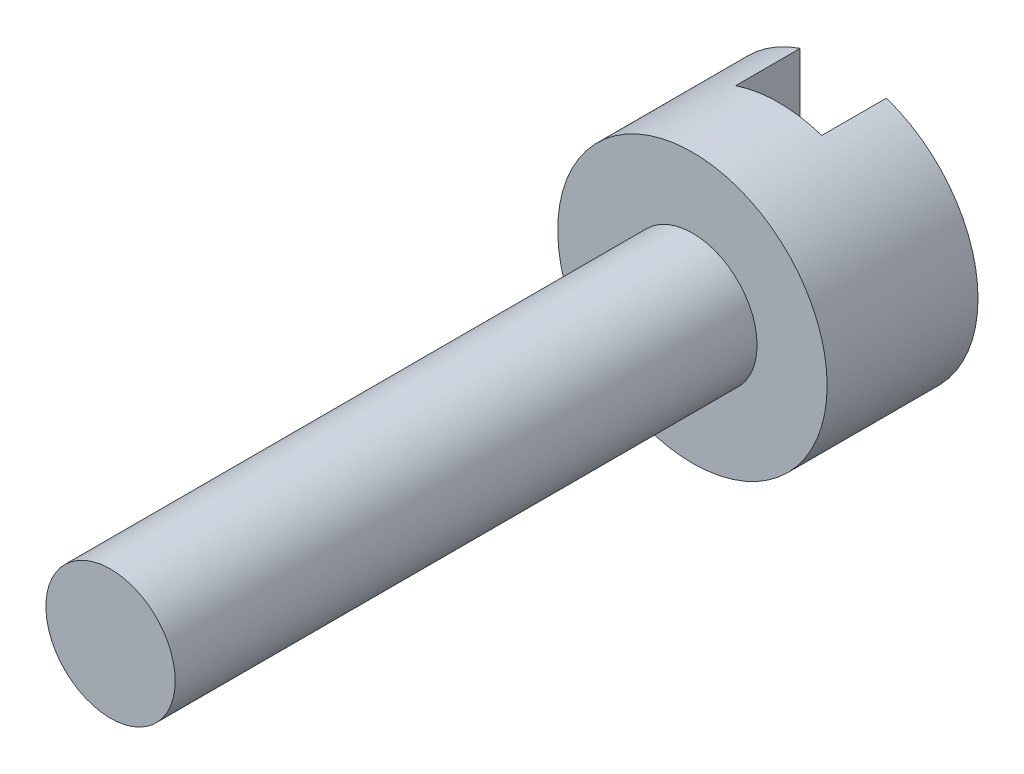
SolidWorks part; units mm, degrees
material "Plain Carbon Steel"
ref_plane "Front Plane" through (0, 0, 0) normal (0, 0, 1) x (1, 0, 0)
ref_plane "Top Plane" through (0, 0, 0) normal (0, 1, 0) x (1, 0, 0)
ref_plane "Right Plane" through (0, 0, 0) normal (1, 0, 0) x (0, 0, -1)
sketch "Sketch1" plane through (0, 0, 0) normal (0, 0, 1) x (1, 0, 0)
  circle A0 centre (0, 0) radius 0.625
  dimension "D1" = 1.25
extrude "Boss-Extrude1" add sketch "Sketch1" along normal blind 0.7
sketch "Sketch3" plane through (0, 0, 0.7) normal (0, 0, 1) x (1, 0, 0)
  circle A0 centre (0, 0) radius 0.3
  dimension "D1" = 0.6
extrude "Boss-Extrude2" add sketch "Sketch3" along normal blind 2.7
sketch "Sketch5" plane through (0, 0, 0) normal (0, 0, -1) x (-1, 0, 0)
  line L1 (-0.2, 1) -> (0.2, 1)
  line L2 (-0.2, 1) -> (-0.2, -1)
  line L3 (-0.2, -1) -> (0.2, -1)
  line L4 (0.2, 1) -> (0.2, -1)
  line L5 (-0.2, 1) -> (0.2, -1) construction
  line L6 (-0.2, -1) -> (0.2, 1) construction
  point P0 (0, 0)
  dimension "D1" = 0.4
  dimension "D2" = 2
extrude "Cut-Extrude1" cut sketch "Sketch5" against normal blind 0.3
